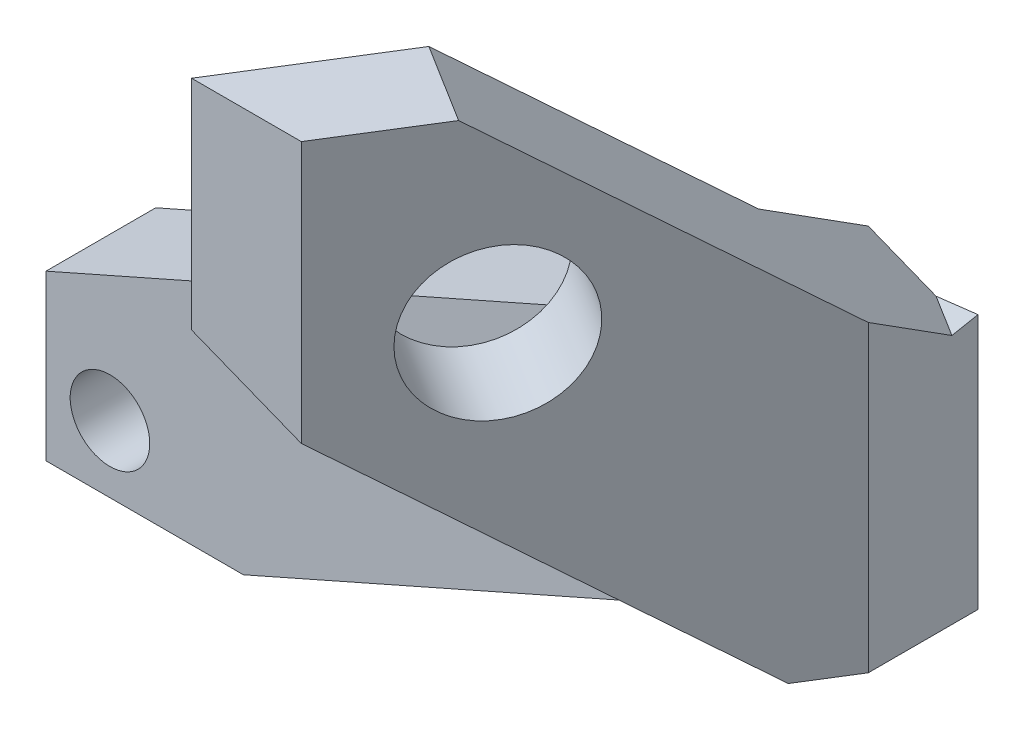
SolidWorks part; units mm, degrees
ref_plane "Přední rovina" through (0, 0, 0) normal (0, 0, 1) x (1, 0, 0)
ref_plane "Horní rovina" through (0, 0, 0) normal (0, 1, 0) x (1, 0, 0)
ref_plane "Pravá rovina" through (0, 0, 0) normal (1, 0, 0) x (0, 0, -1)
sketch "Skica1" plane through (0, 0, 0) normal (0, 0, 1) x (1, 0, 0)
  line L0 (11, 7.9569) -> (11, -1.209)
  line L1 (15, -7.9569) -> (-15, -7.9569) construction
  line L2 (15, -7.9569) -> (15, 7.9569) construction
  line L3 (15, 7.9569) -> (-15, 7.9569) construction
  line L4 (-15, -7.9569) -> (-15, 7.9569) construction
  line L5 (15, -7.9569) -> (-15, 7.9569) construction
  line L6 (15, 7.9569) -> (-15, -7.9569) construction
  line L7 (15, 7.9569) -> (11, 7.9569)
  line L8 (15, 7.9569) -> (15, -1.209)
  line L9 (15, -1.209) -> (11, -1.209)
  line L10 (11, 7.9569) -> (11, -1.209)
  line L11 (11, 7.9569) -> (-14.9719, -3.5145)
  line L12 (11, -1.209) -> (-7.7781, -9.503)
  line L13 (-14.9719, -3.5145) -> (-14.9719, -9.503)
  line L14 (-14.9719, -8.0975) -> (11, 3.3739) construction
  line L15 (-7.7781, -9.503) -> (-14.9719, -9.503)
  circle A0 centre (-12.641, -7.0679) radius 1.45
  point P0 (0, 0)
  dimension "D3" = 2.9
  dimension "D1" = 30
  dimension "D2" = 4
extrude "Přidat vysunutím1" add sketch "Skica1" along normal blind 4 contours L15 L12 L0 L11 L13 A0 | L9 L8 L7 L0
sketch "Skica2" plane through (0, 7.9569, 0) normal (0, 1, 0) x (1, 0, 0)
  line L0 (11, -4) -> (5.5837, -12.6871)
sketch "Skica3" plane through (0, 0, 4) normal (0, 0, 1) x (1, 0, 0)
  line L1 (15, -1.209) -> (11, -1.209)
  line L2 (15, -1.209) -> (15, 7.9569)
  line L3 (15, 7.9569) -> (11, 7.9569)
  line L4 (11, -1.209) -> (11, 7.9569)
extrude "Přidat vysunutím2" add sketch "Skica3" along direction (-0.5291, 0, 0.8486) on the side of the normal blind 15
sketch "Skica5" plane through (0, 7.9569, 0) normal (0, 1, 0) x (1, 0, 0)
  line L6 (15, 0) -> (11, 0)
  line L7 (11, 0) -> (11, -4)
  line L8 (11, -4) -> (3.0639, -16.7286)
  line L9 (3.0639, -16.7286) -> (7.0639, -16.7286)
  line L10 (7.0639, -16.7286) -> (15, -4)
  line L11 (15, -4) -> (15, 0)
  line L12 (15, 0) -> (11, 0)
  line L13 (11, 0) -> (11, -4)
  line L14 (11, -4) -> (3.0639, -16.7286)
  line L15 (3.0639, -16.7286) -> (7.0639, -16.7286)
  line L16 (7.0639, -16.7286) -> (15, -4)
  line L17 (15, -4) -> (15, 0)
  dimension "D1" = 0
extrude "Přidat vysunutím3" add sketch "Skica5" along normal blind 10
sketch "Skica6" plane through (9.7167, 0, 6.0582) normal (-0.8486, 0, -0.5291) x (-0.5291, 0, 0.8486)
  line L0 (-2.4255, -1.209) -> (12.5745, 10.0096)
  line L1 (12.5745, 17.9569) -> (12.5745, -1.209) construction
  line L2 (12.5745, 10.0096) -> (12.5745, 17.9569)
  line L3 (12.5745, 17.9569) -> (6.2967, 17.9569)
  line L5 (6.2967, 17.9569) -> (-7.128, 7.9165)
  line L6 (-7.128, 7.9165) -> (-11.685, 8.9453)
  line L7 (-11.685, 8.9453) -> (-10.1799, 18.6304)
  line L8 (-10.1799, 18.6304) -> (-8.9675, 18.6304)
  line L9 (-8.9675, 18.6304) -> (19.1687, 18.6304)
  line L10 (19.1687, 18.6304) -> (19.6704, -6.5579)
  line L11 (19.6704, -6.5579) -> (0.4809, -6.5579)
  line L12 (0.4809, -6.5579) -> (-2.4255, -1.209)
  point P5 (0, 0)
  point P9 (7.0699, 17.9569)
  point P10 (0, 0)
  point P18 (5.0745, 17.9569)
  point P19 (0, 0)
extrude "Odebrat vysunutím2" cut sketch "Skica6" against normal blind 10
sketch "Skica7" plane through (9.7167, 0, 6.0582) normal (0.8486, 0, 0.5291) x (0.5291, 0, -0.8486)
  line L5 (2.4255, 17.9569) -> (2.4255, 11.4335)
  line L6 (2.4255, 11.4335) -> (7.128, 7.9165)
  line L7 (7.128, 7.9165) -> (7.1393, 7.919)
  line L8 (7.1393, 7.919) -> (7.1393, 17.9569)
  line L9 (7.1393, 17.9569) -> (2.4255, 17.9569)
  line L10 (2.4255, 17.9569) -> (2.4255, 11.4335)
  line L11 (2.4255, 11.4335) -> (7.128, 7.9165)
  line L12 (7.128, 7.9165) -> (7.1393, 7.919)
  line L13 (7.1393, 7.919) -> (7.1393, 17.9569)
  line L14 (7.1393, 17.9569) -> (2.4255, 17.9569)
  dimension "D1" = 0
extrude "Odebrat vysunutím3" cut sketch "Skica7" against normal blind 10
sketch "Skica8" plane through (9.7167, 0, 6.0582) normal (-0.8486, 0, -0.5291) x (-0.5291, 0, 0.8486)
  circle A0 centre (5.2579, 11.0906) radius 2.75
  point P2 (5.2579, 11.0906)
  dimension "D1" = 5.5
extrude "Odebrat vysunutím4" cut sketch "Skica8" against normal blind 10
